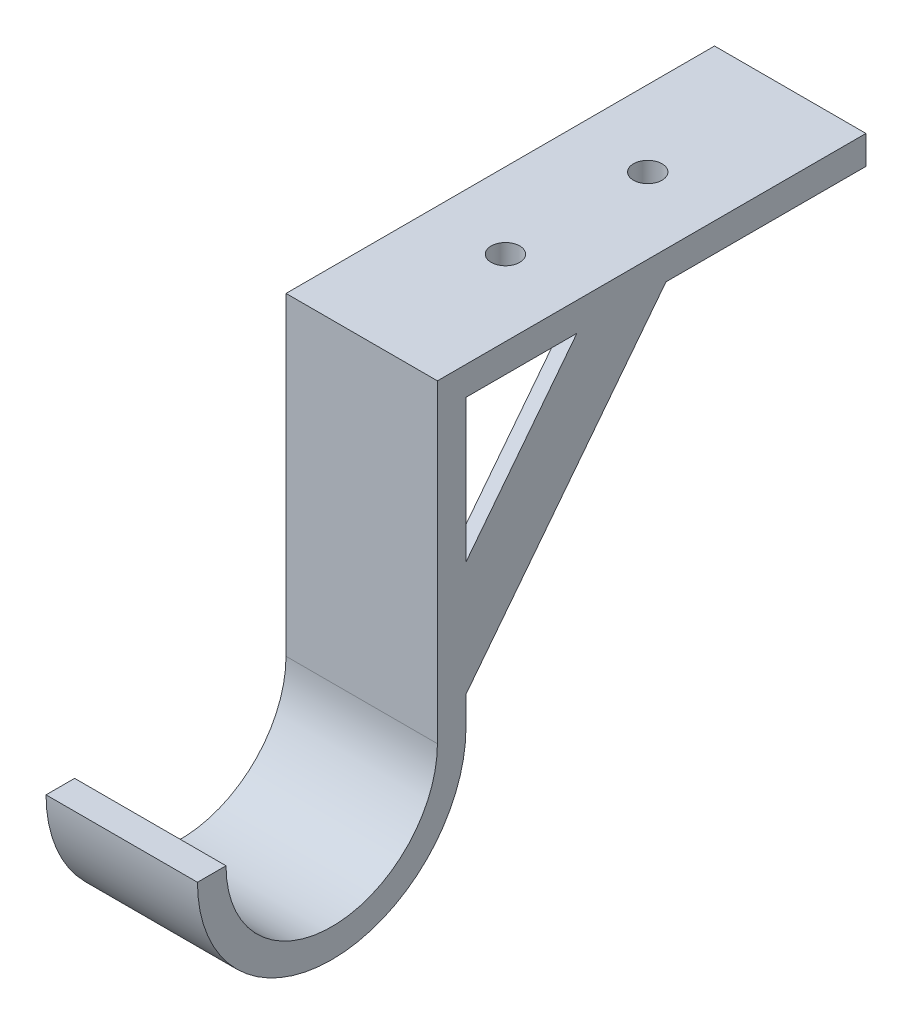
SolidWorks part; units mm, degrees
ref_plane "Front Plane" through (0, 0, 0) normal (0, 0, 1) x (1, 0, 0)
ref_plane "Top Plane" through (0, 0, 0) normal (0, 1, 0) x (1, 0, 0)
ref_plane "Right Plane" through (0, 0, 0) normal (1, 0, 0) x (0, 0, -1)
sketch "Sketch1" plane through (0, 0, 0) normal (0, 1, 0) x (1, 0, 0)
  line L0 (0, 0) -> (6.731, 0)
  line L1 (0, 0) -> (-6.731, 0)
  line L2 (6.731, 0) -> (6.731, 38.1)
  line L3 (6.731, 38.1) -> (-6.731, 38.1)
  line L4 (-6.731, 38.1) -> (-6.731, 0)
  dimension "D1" = 6.731
  dimension "D2" = 6.731
  dimension "D3" = 38.1
extrude "Boss-Extrude1" add sketch "Sketch1" along normal blind 2.54
sketch "Sketch2" plane through (0, 2.54, 0) normal (0, 1, 0) x (1, 0, 0)
  line L0 (0, 38.1) -> (0, 25.4291)
  line L3 (6.731, 38.1) -> (-6.731, 38.1) construction
  line L4 (0, 0) -> (0, 12.7763)
  circle A0 centre (0, 25.4291) radius 1.27
  circle A1 centre (0, 12.7763) radius 1.27
  dimension "D1" = 2.54
  dimension "D2" = 2.54
extrude "Cut-Extrude1" cut sketch "Sketch2" against normal blind 5.334
sketch "Sketch3" plane through (0, 0, 0) normal (0, 0, 1) x (1, 0, 0)
  line L0 (-6.731, 2.54) -> (-6.731, -25.4)
  line L1 (-6.731, -25.4) -> (6.731, -25.4)
  line L2 (6.731, -25.4) -> (6.731, 2.54)
  line L3 (-6.731, 2.54) -> (6.731, 2.54) construction
  line L4 (6.731, 2.54) -> (6.731, 0) construction
  line L5 (-6.731, 2.54) -> (6.731, 2.54)
  dimension "D1" = 27.94
extrude "Boss-Extrude2" add sketch "Sketch3" against normal blind 2.54
sketch "Sketch4" plane through (-6.731, 0, 0) normal (-1, 0, 0) x (0, 0, 1)
  line L5 (-2.54, -25.4) -> (0, -25.4)
  line L6 (18.796, -25.4) -> (21.336, -25.4)
  arc A0 (0, -25.4) -> (18.796, -25.4) centre (9.398, -25.4) ccw
  arc A2 (-2.54, -25.4) -> (21.336, -25.4) centre (9.398, -25.4) ccw
  dimension "D1" = 9.398
extrude "Boss-Extrude3" add sketch "Sketch4" against normal blind 13.462
sketch "Sketch5" plane through (6.731, 0, 0) normal (1, 0, 0) x (0, 0, -1)
  line L7 (-18.796, -25.4) -> (-21.336, -25.4)
  line L8 (-18.796, -25.4) -> (-21.336, -25.4)
  line L13 (2.54, -25.4) -> (2.54, 0)
  line L14 (2.54, 0) -> (38.1, 0)
  line L15 (38.1, 0) -> (38.1, 2.54)
  line L16 (38.1, 2.54) -> (0, 2.54)
  line L17 (0, 2.54) -> (0, -25.4)
  arc A2 (-18.796, -25.4) -> (0, -25.4) centre (-9.398, -25.4) ccw
  arc A3 (-21.336, -25.4) -> (2.54, -25.4) centre (-9.398, -25.4) ccw
  arc A4 (-21.336, -25.4) -> (2.54, -25.4) centre (-9.398, -25.4) ccw
  dimension "D1" = 0
sketch "Sketch8" plane through (6.731, 0, 0) normal (1, 0, 0) x (0, 0, -1)
  line L0 (2.54, -22.86) -> (20.32, 0)
  line L1 (2.54, 0) -> (38.1, 0) construction
  line L2 (2.54, -22.86) -> (2.54, -12.6784)
  line L3 (2.54, -25.4) -> (2.54, 0) construction
  line L4 (2.54, -12.6784) -> (12.401, 0)
  line L5 (12.401, 0) -> (20.32, 0)
extrude "Boss-Extrude7" add sketch "Sketch8" against normal blind 1.27
sketch "Sketch9" plane through (-6.731, 0, 0) normal (-1, 0, 0) x (0, 0, 1)
  line L7 (-2.54, -12.6784) -> (-2.54, -22.86)
  line L8 (-2.54, -22.86) -> (-20.32, 0)
  line L9 (-38.1, 0) -> (-2.54, 0) construction
  line L10 (-20.32, 0) -> (-12.401, 0)
  line L11 (-20.32, 0) -> (-12.401, 0) construction
  line L12 (-12.401, 0) -> (-2.54, -12.6784)
extrude "Boss-Extrude12" add sketch "Sketch9" against normal blind 1.27
